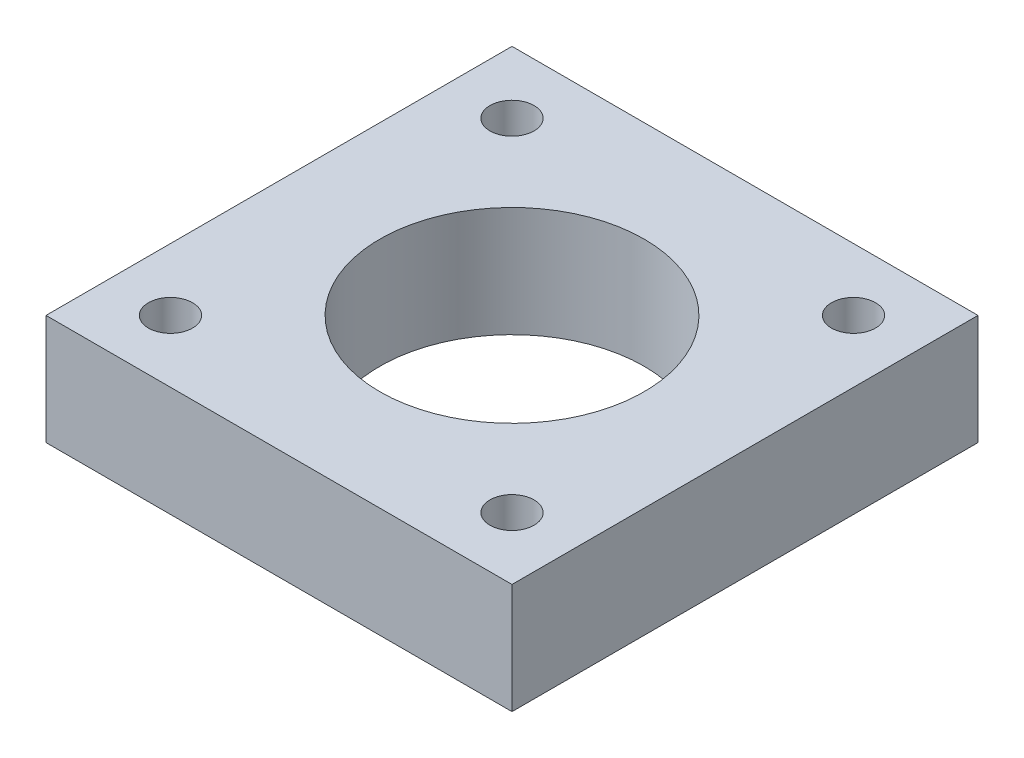
SolidWorks part; units mm, degrees
ref_plane "Front Plane" through (0, 0, 0) normal (0, 0, 1) x (1, 0, 0)
ref_plane "Top Plane" through (0, 0, 0) normal (0, 1, 0) x (1, 0, 0)
ref_plane "Right Plane" through (0, 0, 0) normal (1, 0, 0) x (0, 0, -1)
sketch "Sketch1" plane through (0, 0, 0) normal (0, 1, 0) x (1, 0, 0)
  line L1 (-21.15, 21.15) -> (21.15, 21.15)
  line L2 (-21.15, 21.15) -> (-21.15, -21.15)
  line L3 (-21.15, -21.15) -> (21.15, -21.15)
  line L4 (21.15, 21.15) -> (21.15, -21.15)
  line L5 (-21.15, 21.15) -> (21.15, -21.15) construction
  line L6 (-21.15, -21.15) -> (21.15, 21.15) construction
  line L7 (-15.5, 15.5) -> (15.5, 15.5) construction
  line L8 (-15.5, 15.5) -> (-15.5, -15.5) construction
  line L9 (-15.5, -15.5) -> (15.5, -15.5) construction
  line L10 (15.5, 15.5) -> (15.5, -15.5) construction
  line L11 (-15.5, 15.5) -> (15.5, -15.5) construction
  line L12 (-15.5, -15.5) -> (15.5, 15.5) construction
  circle A0 centre (15.5, 15.5) radius 2
  circle A1 centre (15.5, -15.5) radius 2
  circle A2 centre (-15.5, 15.5) radius 2
  circle A3 centre (-15.5, -15.5) radius 2
  circle A4 centre (0, 0) radius 12
  point P0 (0, 0)
  point P6 (0, 0)
  dimension "D1" = 4
  dimension "D4" = 24
  dimension "D2" = 31
  dimension "D3" = 42.3
extrude "Boss-Extrude1" add sketch "Sketch1" along normal blind 10
